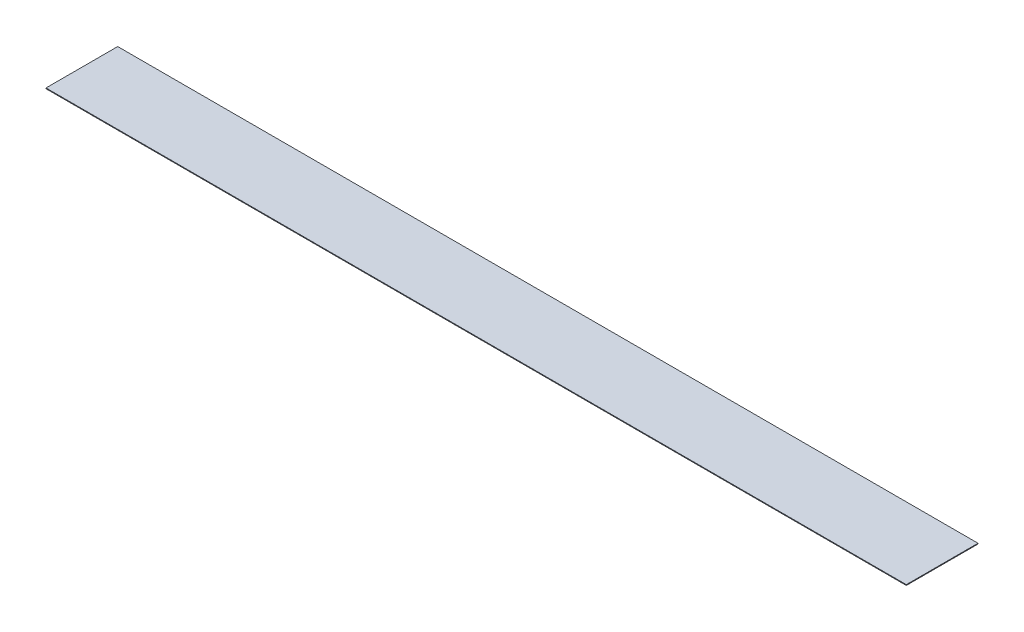
SolidWorks part; units mm, degrees
other "Markup1"
sketch "Sketch6" plane through (114.3, 38.1, 139.7) normal (0.0122, 0.8279, 0.5607) x (0.9984, -0.0412, 0.0392)
material "Ceramic Porcelain"
ref_plane "Front Plane" through (0, 0, 0) normal (0, 0, 1) x (1, 0, 0)
ref_plane "Top Plane" through (0, 0, 0) normal (0, 1, 0) x (1, 0, 0)
ref_plane "Right Plane" through (0, 0, 0) normal (1, 0, 0) x (0, 0, -1)
sketch "Sketch7" plane through (0, 0, 0) normal (0, 1, 0) x (1, 0, 0)
  line L1 (-1524, -127) -> (1524, -127)
  line L2 (-1524, -127) -> (-1524, 127)
  line L3 (-1524, 127) -> (1524, 127)
  line L4 (1524, -127) -> (1524, 127)
  line L5 (-1524, -127) -> (1524, 127) construction
  line L6 (-1524, 127) -> (1524, -127) construction
  point P0 (0, 0)
  dimension "D1" = 3048
  dimension "D2" = 254
extrude "Boss-Extrude1" add sketch "Sketch7" along normal blind 2.54
